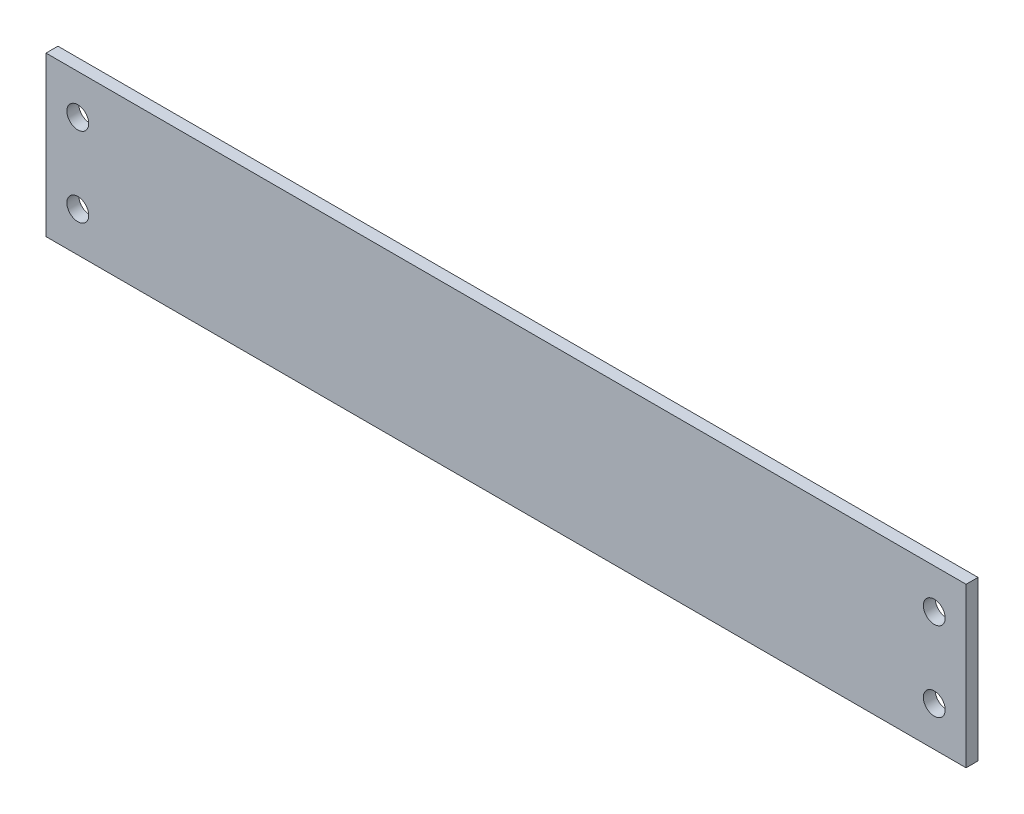
SolidWorks part; units mm, degrees
ref_plane "Front Plane" through (0, 0, 0) normal (0, 0, 1) x (1, 0, 0)
ref_plane "Top Plane" through (0, 0, 0) normal (0, 1, 0) x (1, 0, 0)
ref_plane "Right Plane" through (0, 0, 0) normal (1, 0, 0) x (0, 0, -1)
sketch "Extrusion Base Sketch" plane through (0, 0, 0) normal (0, 0, 1) x (1, 0, 0)
  line L0 (209.5, 36.75) -> (209.5, -3.25)
  line L1 (0, 0) -> (187.5, 0) construction
  line L2 (0, 0) -> (0, 33.5) construction
  line L3 (0, 33.5) -> (187.5, 33.5) construction
  line L4 (187.5, 0) -> (187.5, 33.5) construction
  line L5 (-22, 36.75) -> (209.5, 36.75)
  line L6 (-3.25, 36.75) -> (-3.25, -3.25) construction
  line L7 (-22, -3.25) -> (209.5, -3.25)
  line L8 (190.75, 36.75) -> (190.75, -3.25) construction
  line L9 (-22, 36.75) -> (-22, -3.25)
  line L10 (201.5, 26.75) -> (201.5, 6.75) construction
  line L11 (201.5, 16.75) -> (209.5, 16.75) construction
  line L12 (-14, 26.75) -> (-14, 6.75) construction
  dimension "D1" = 33.5
  dimension "D2" = 187.5
  dimension "D4" = 3.25
  dimension "D5" = 3.25
  dimension "D6" = 3.25
  dimension "D3" = 40
extrude "Extrusion Base Extrude" add sketch "Extrusion Base Sketch" against normal blind 3
hole_wizard "M5 Mounting Holes" positions "M5 Mounting Holes Position Sketch" profile "M5 Mounting Holes Profile Sketch" hole size "M5" standard "ANSI Metric" end condition through all
sketch "M5 Mounting Holes Position Sketch" plane through (0, 0, -3) normal (0, 0, -1) x (-1, 0, 0)
  point P0 (-201.5, 26.75)
  point P2 (-201.5, 6.75)
  point P4 (14, 26.75)
  point P6 (14, 6.75)
sketch "M5 Mounting Holes Profile Sketch" plane through (201.5, 26.75, -3) normal (1, 0, 0) x (0, 1, 0)
  line L0 (0, 0) -> (0, 3)
  line L1 (0, 3) -> (2.75, 3)
  line L2 (2.75, 3) -> (2.75, 0)
  line L5 (2.75, 0) -> (0, 0)
  line L11 (0, -6.35) -> (0, 107.95) construction
  dimension "Thru Hole Dia." = 5.5
  dimension "Thru Hole Depth" = 3
equation "\"Logo Height\"= 33.5mm"
equation "\"Total Height\"= 40mm"
equation "\"Border\"= ( \"Total Height\" - \"Logo Height\" ) / 2"
equation "\"Logo Length\"= 187.5mm"
equation "\"D1@Extrusion Base Sketch\" = \"Logo Height\""
equation "\"D2@Extrusion Base Sketch\" = \"Logo Length\""
equation "\"D4@Extrusion Base Sketch\" = \"Border\""
equation "\"D5@Extrusion Base Sketch\" = \"Border\""
equation "\"D6@Extrusion Base Sketch\" = \"Border\""
equation "\"D3@Extrusion Base Sketch\" = \"Total Height\""
